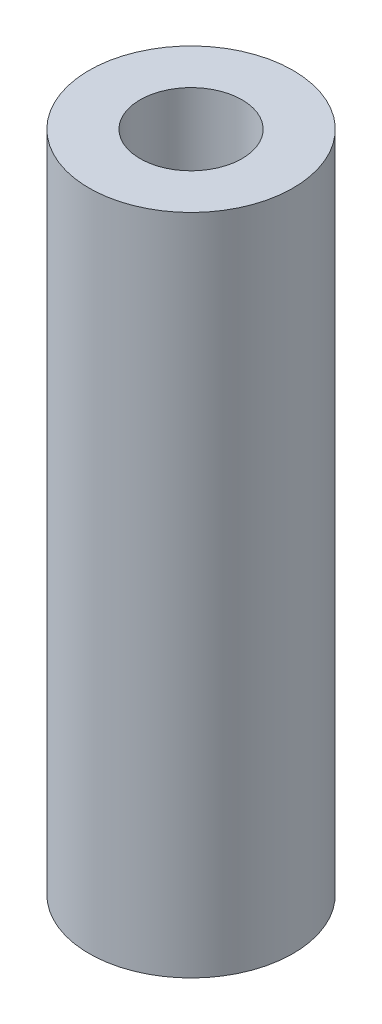
SolidWorks part; units mm, degrees
material "5052-H34"
ref_plane "Front Plane" through (0, 0, 0) normal (0, 0, 1) x (1, 0, 0)
ref_plane "Top Plane" through (0, 0, 0) normal (0, 1, 0) x (1, 0, 0)
ref_plane "Right Plane" through (0, 0, 0) normal (1, 0, 0) x (0, 0, -1)
sketch "Sketch1" plane through (0, 0, 0) normal (0, 1, 0) x (1, 0, 0)
  circle A0 centre (0, 0) radius 2
  circle A1 centre (0, 0) radius 1
  dimension "D1" = 1
  dimension "D2" = 2
extrude "Boss-Extrude1" add sketch "Sketch1" along normal mid plane 13
